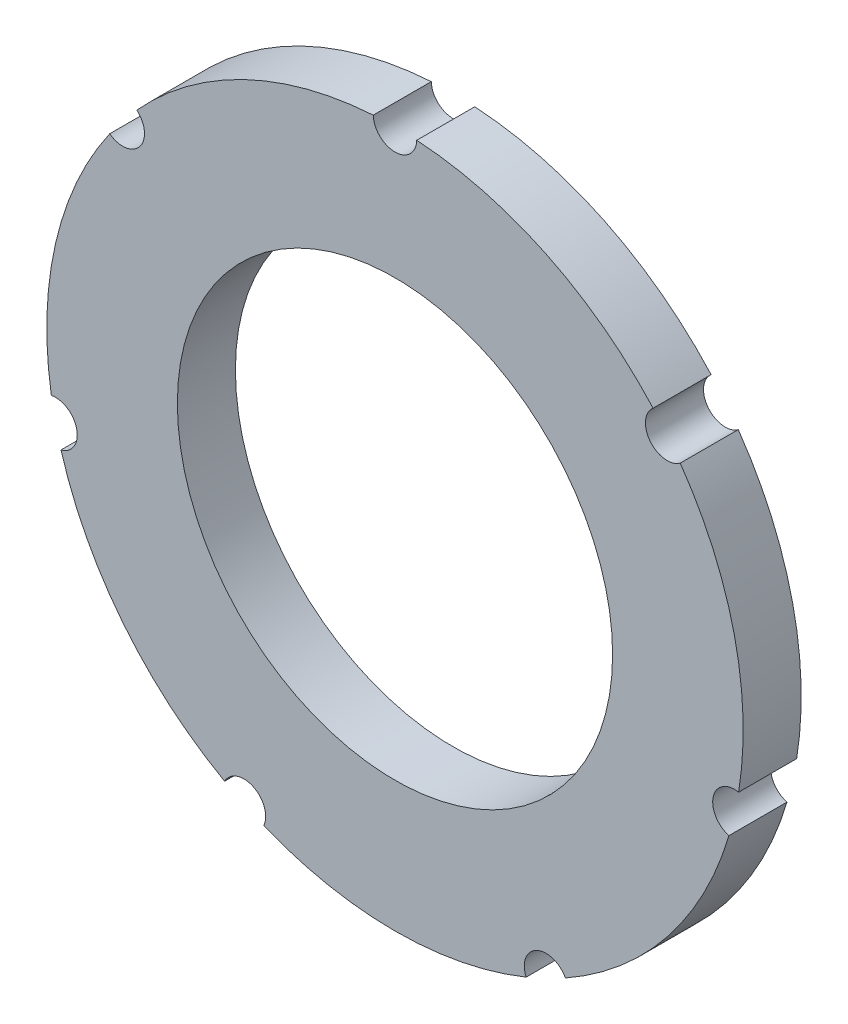
SolidWorks part; units mm, degrees
material "Alloy Steel (SS)"
ref_plane "Front Plane" through (0, 0, 0) normal (0, 0, 1) x (1, 0, 0)
ref_plane "Top Plane" through (0, 0, 0) normal (0, 1, 0) x (1, 0, 0)
ref_plane "Right Plane" through (0, 0, 0) normal (1, 0, 0) x (0, 0, -1)
sketch "Sketch1" plane through (0, 0, 0) normal (0, 0, 1) x (1, 0, 0)
  arc A2 (-1.4993, 23.9531) -> (-17.7925, 16.1067) centre (0, 0) ccw
  circle A3 centre (0, 0) radius 22.5 construction
  arc A4 (-1.4993, 23.9531) -> (1.4993, 23.9531) centre (0, 24) ccw
  arc A5 (17.7925, 16.1067) -> (19.6621, 13.7624) centre (18.764, 14.9638) ccw
  arc A6 (23.6862, -3.8684) -> (23.019, -6.7917) centre (23.3983, -5.3405) ccw
  arc A7 (11.7437, -20.9305) -> (9.0421, -22.2315) centre (10.4132, -21.6233) ccw
  arc A8 (-9.0421, -22.2315) -> (-11.7437, -20.9305) centre (-10.4132, -21.6233) ccw
  arc A9 (-23.019, -6.7917) -> (-23.6862, -3.8684) centre (-23.3983, -5.3405) ccw
  arc A10 (-19.6621, 13.7624) -> (-17.7925, 16.1067) centre (-18.764, 14.9638) ccw
  arc A11 (-19.6621, 13.7624) -> (-23.6862, -3.8684) centre (0, 0) ccw
  arc A12 (-23.019, -6.7917) -> (-11.7437, -20.9305) centre (0, 0) ccw
  arc A13 (-9.0421, -22.2315) -> (9.0421, -22.2315) centre (0, 0) ccw
  arc A14 (11.7437, -20.9305) -> (23.019, -6.7917) centre (0, 0) ccw
  arc A15 (23.6862, -3.8684) -> (19.6621, 13.7624) centre (0, 0) ccw
  arc A16 (17.7925, 16.1067) -> (1.4993, 23.9531) centre (0, 0) ccw
  circle A17 centre (0, 0) radius 15
  point P27 (0, 0)
  dimension "D3" = 48
  dimension "D4" = 45
  dimension "D1" = 30
  dimension "D2" = 7
extrude "Boss-Extrude1" add sketch "Sketch1" along normal blind 4
cosmetic thread "Cosmetic Thread1" parameters "D2"=30.05
ref_plane "Plane1" through (0, 0, 0) normal (0, 0, -1) x (-1, 0, 0)
equation "\"OuterHousingDiameter\"= 30"
equation "\"D1@Sketch1\"=\"OuterHousingDiameter\""
equation "\"D4@Sketch1\"=\"OuterHousingDiameter\"+15"
equation "\"D3@Sketch1\"=\"OuterHousingDiameter\"+18"
equation "\"D2@Cosmetic Thread1\"=\"OuterHousingDiameter\"+0.05"
